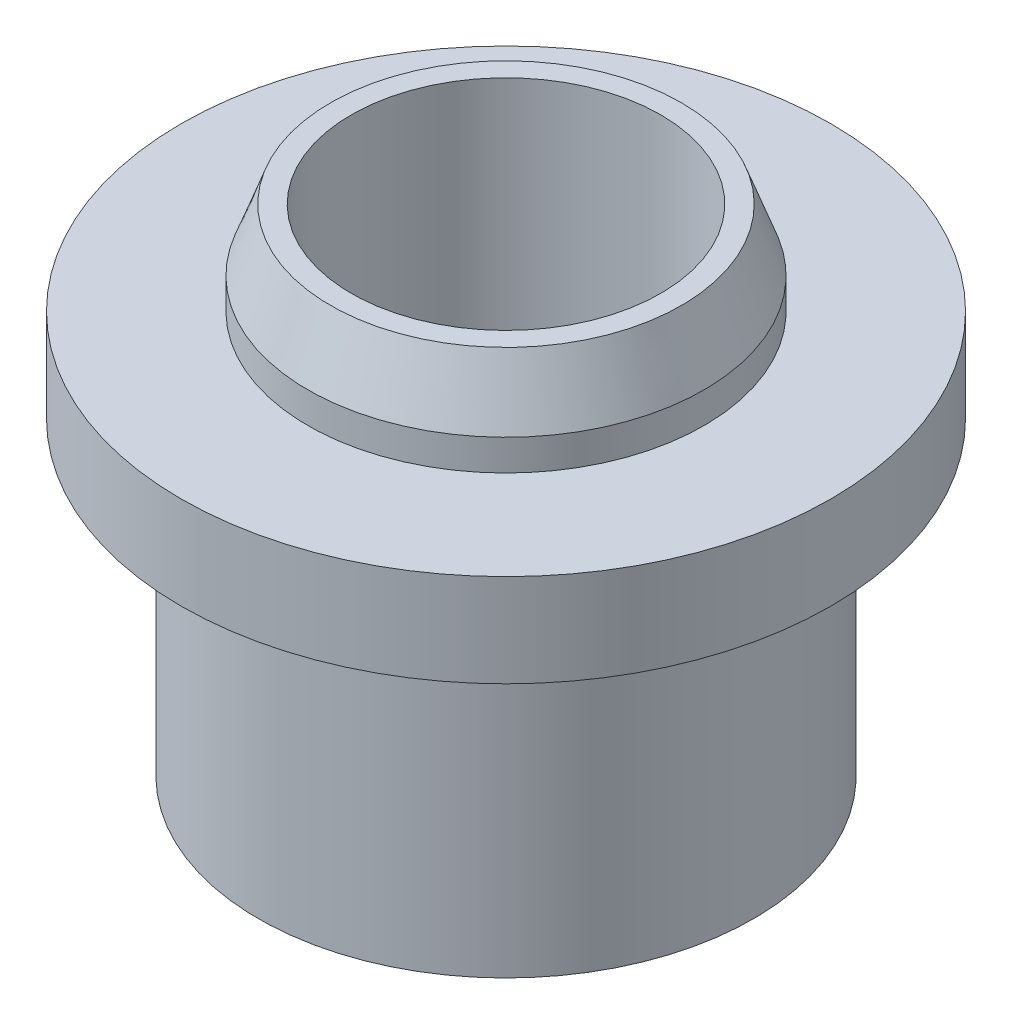
SolidWorks part; units mm, degrees
ref_plane "Front Plane" through (0, 0, 0) normal (0, 0, 1) x (1, 0, 0)
ref_plane "Top Plane" through (0, 0, 0) normal (0, 1, 0) x (1, 0, 0)
ref_plane "Right Plane" through (0, 0, 0) normal (1, 0, 0) x (0, 0, -1)
sketch "Sketch1" plane through (0, 0, 0) normal (0, 0, 1) x (1, 0, 0)
  line L0 (0, 0) -> (0, 5.4195) construction
  line L1 (2.5, -0.0763) -> (2.5, 6.4237)
  line L2 (3.2, 6.4237) -> (5.25, 6.4237)
  line L3 (5.25, 6.4237) -> (5.25, 4.9237)
  line L4 (5.25, 4.9237) -> (4, 4.9237)
  line L5 (4, 4.9237) -> (4, -0.0763)
  line L6 (4, -0.0763) -> (2.5, -0.0763)
  line L7 (2.5, 6.4237) -> (2.5, 7.9237)
  line L8 (2.5, 7.9237) -> (2.836, 7.9237)
  line L10 (2.836, 7.9237) -> (3.2, 6.9237)
  line L11 (3.2, 6.9237) -> (3.2, 6.4237)
  point P13 (0, 0)
  point P14 (2.5, 7.4237)
  dimension "D1" = 8
  dimension "D2" = 5
  dimension "D3" = 1.5
  dimension "D4" = 5
  dimension "D5" = 10.5
  dimension "D6" = 3.2
  dimension "D7" = 1.5
  dimension "D8" = 110
  dimension "D9" = 0.5
revolve "Revolve1" add sketch "Sketch1" angle 360 about L0
